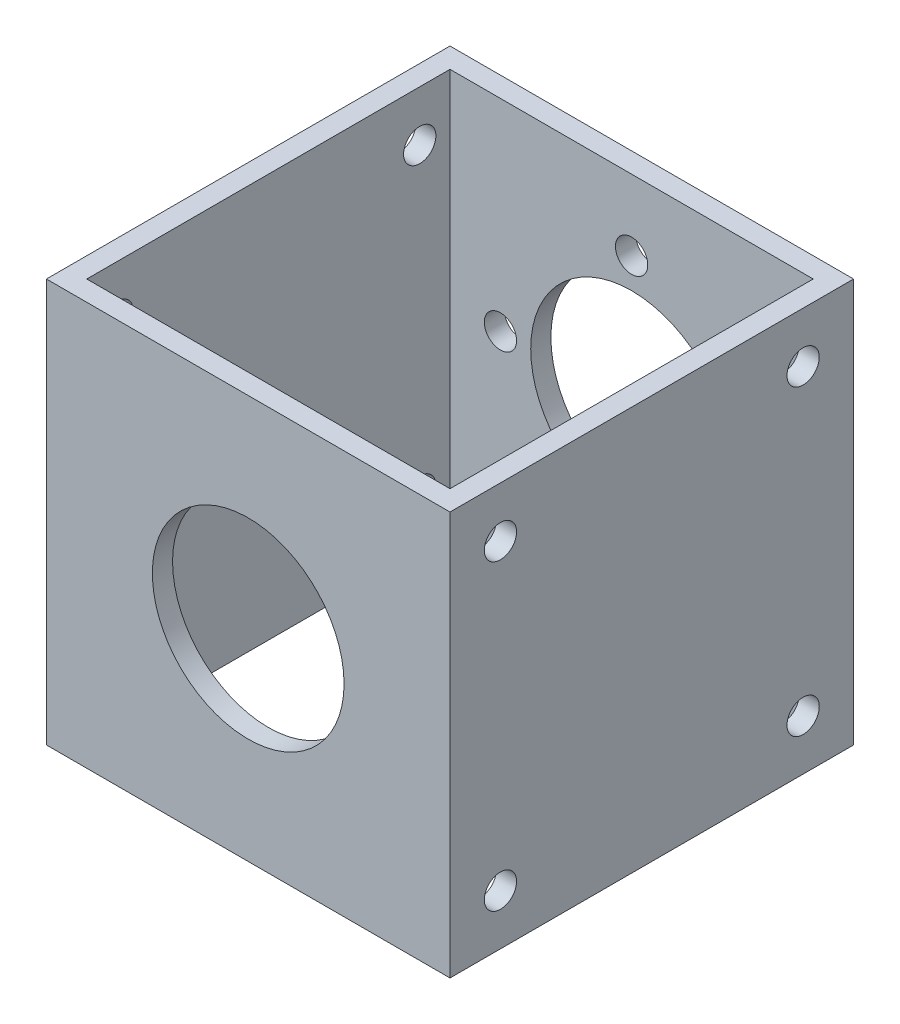
SolidWorks part; units mm, degrees
ref_plane "正面" through (0, 0, 0) normal (0, 0, 1) x (1, 0, 0)
ref_plane "平面" through (0, 0, 0) normal (0, 1, 0) x (1, 0, 0)
ref_plane "右側面" through (0, 0, 0) normal (1, 0, 0) x (0, 0, -1)
sketch "ｽｹｯﾁ1" plane through (0, 0, 0) normal (0, 1, 0) x (1, 0, 0)
  line L0 (-18, 18) -> (18, 18)
  line L1 (-20, 20) -> (20, 20)
  line L2 (-20, 20) -> (-20, -20)
  line L3 (-20, -20) -> (20, -20)
  line L4 (20, 20) -> (20, -20)
  line L5 (-20, 20) -> (20, -20) construction
  line L6 (-20, -20) -> (20, 20) construction
  line L7 (18, 18) -> (18, -18)
  line L8 (-18, -18) -> (18, -18)
  line L9 (-18, 18) -> (-18, -18)
  point P0 (0, 0)
  dimension "D1" = 40
  dimension "D2" = 40
  dimension "D3" = 2
extrude "ﾎﾞｽ - 押し出し1" add sketch "ｽｹｯﾁ1" along normal blind 40
sketch "ｽｹｯﾁ2" plane through (0, 0, -20) normal (0, 0, -1) x (-1, 0, 0)
  line L0 (20, 40) -> (20, 0) construction
  line L1 (-20, 0) -> (20, 0) construction
  circle A0 centre (0, 20) radius 10
  circle A2 centre (0, 33) radius 1.6
  circle A3 centre (13, 20) radius 1.6
  circle A4 centre (0, 7) radius 1.6
  circle A5 centre (-13, 20) radius 1.6
  point P18 (0, 20)
  dimension "D1" = 20
  dimension "D2" = 20
  dimension "D3" = 4
extrude "ｶｯﾄ - 押し出し1" cut sketch "ｽｹｯﾁ2" against normal up to next
sketch "ｽｹｯﾁ3" plane through (0, 0, 20) normal (0, 0, 1) x (1, 0, 0)
  line L0 (-20, 0) -> (20, 0) construction
  line L1 (20, 40) -> (20, 0) construction
  circle A0 centre (0, 20) radius 9.5
  dimension "D1" = 20
  dimension "D2" = 20
  dimension "D3" = 19
extrude "ｶｯﾄ - 押し出し2" cut sketch "ｽｹｯﾁ3" against normal up to next
sketch "ｽｹｯﾁ4" plane through (-20, 0, 0) normal (-1, 0, 0) x (0, 0, 1)
  line L0 (0, 40) -> (0, 0) construction
  line L1 (-20, 40) -> (20, 40) construction
  line L2 (20, 20) -> (-20, 20) construction
  line L3 (20, 40) -> (20, 0) construction
  line L4 (-20, 40) -> (-20, 0) construction
  line L5 (-20, 0) -> (20, 0) construction
  circle A0 centre (15, 5) radius 1.6
  circle A1 centre (-15, 5) radius 1.6
  circle A2 centre (15, 35) radius 1.6
  circle A3 centre (-15, 35) radius 1.6
  dimension "D1" = 5
  dimension "D2" = 5
extrude "ｶｯﾄ - 押し出し3" cut sketch "ｽｹｯﾁ4" against normal through all
